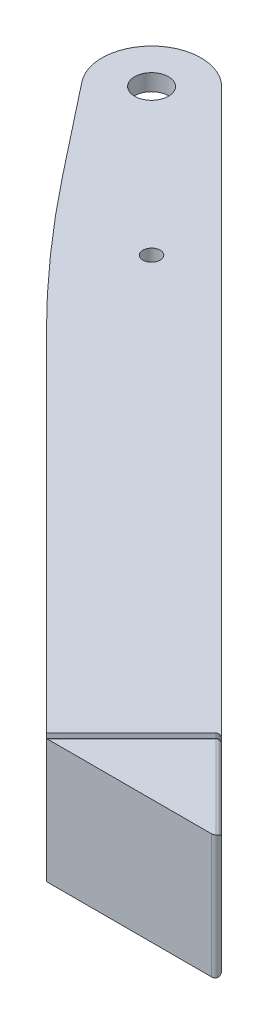
SolidWorks part; units mm, degrees
material "ABS"
ref_plane "前视基准面" through (0, 0, 0) normal (0, 0, 1) x (1, 0, 0)
ref_plane "上视基准面" through (0, 0, 0) normal (0, 1, 0) x (1, 0, 0)
ref_plane "右视基准面" through (0, 0, 0) normal (1, 0, 0) x (0, 0, -1)
other "Configuration Table"
sketch "草图2" plane through (0, 0, 0) normal (0, 1, 0) x (1, 0, 0)
  line L0 (136.9292, -162.3851) -> (179.3556, -162.3851)
  line L2 (8.4853, 8.4853) -> (179.3556, -162.3851)
  line L3 (0, 0) -> (35.3553, -35.3553) construction
  line L4 (35.3553, -35.3553) -> (191.9802, -191.9802) construction
  line L5 (191.9802, -191.9802) -> (389.2035, -389.2035) construction
  line L6 (-190.91, 190.91) -> (0, 0) construction
  line L7 (136.9292, -162.3851) -> (22.6274, -48.0833)
  line L8 (22.6274, -48.0833) -> (-9.4236, -7.4294)
  line L9 (22.6274, -48.0833) -> (35.3553, -35.3553) construction
  circle A0 centre (0, 0) radius 4.1
  circle A1 centre (35.3553, -35.3553) radius 2.1
  arc A3 (-9.4236, -7.4294) -> (8.4853, 8.4853) centre (0, 0) cw
  point P16 (158.1424, -162.3851)
  dimension "D2" = 12
  dimension "D3" = 8.2
  dimension "D4" = 4.2
  dimension "D5" = 50
  dimension "D1" = 226.667
  dimension "D6" = 45
  dimension "D7" = 30
extrude "凸台-拉伸1" add sketch "草图2" along normal blind 4 contours A0 | A1 | L2 L0 L7 L8 A3
fillet "圆角1" radius 400 1 edges at (22.6274, 2, 48.0833)
sketch "草图6" plane through (-12.7279, 0, 12.7279) normal (-0.7071, 0, 0.7071) x (0.7071, 0, 0.7071)
  line L0 (191.6471, 4) -> (191.6471, 0)
  line L1 (191.6471, 0) -> (211.6471, -13)
  line L2 (211.6471, -13) -> (211.6471, 17)
  line L3 (211.6471, 17) -> (191.6471, 4)
  line L4 (211.6471, 4) -> (73.5829, 4) construction
  line L5 (211.6471, 0) -> (73.5829, 0) construction
  line L8 (73.5829, 0) -> (211.6471, 0)
  line L9 (211.6471, 0) -> (211.6471, 4)
  line L10 (211.6471, 4) -> (73.5829, 4)
  line L11 (73.5829, 4) -> (73.5829, 0)
  line L12 (73.5829, 0) -> (211.6471, 0) construction
  line L14 (211.6471, 4) -> (73.5829, 4) construction
  line L15 (73.5829, 4) -> (73.5829, 0) construction
  line L26 (211.6471, 0) -> (211.6471, 4) construction
  dimension "D1" = 30
  dimension "D2" = 0
  dimension "D3" = 20
  dimension "D4" = 13
extrude "凸台-拉伸4" add sketch "草图6" against normal up to surface (30 mm away) up to face at (93.9204, 2, 76.9499)
sketch "草图8" plane through (149.6571, 0, 149.6571) normal (0.7071, 0, 0.7071) x (0.7071, 0, -0.7071)
  line L0 (-18, 4) -> (12, 4) construction
  line L1 (12, 4) -> (12, 17) construction
  line L2 (12, 17) -> (-18, 17) construction
  line L3 (-18, 17) -> (-18, 4) construction
  line L4 (12, -13) -> (12, 0) construction
  line L5 (12, 0) -> (-18, 0) construction
  line L6 (-18, 0) -> (-18, -13) construction
  line L7 (-18, -13) -> (12, -13) construction
  line L8 (-18, 4) -> (12, 4)
  line L9 (12, 4) -> (12, 17)
  line L10 (12, 17) -> (-18, 17)
  line L11 (-18, 17) -> (-18, 4)
  line L12 (12, -13) -> (12, 0)
  line L13 (12, 0) -> (-18, 0)
  line L14 (-18, 0) -> (-18, -13)
  line L15 (-18, -13) -> (12, -13)
extrude "凸台-拉伸5" add sketch "草图8" along normal up to surface (30 mm away)
fillet "圆角5" radius 1 7 edges at (151.0713, -6.5, 134.1008) (151.0713, 10.5, 134.1008) (147.5358, -13, 151.7785) (168.749, -13, 151.7785) (179.3556, 2, 162.3851) (168.749, 17, 151.7785) (147.5358, 17, 151.7785)
